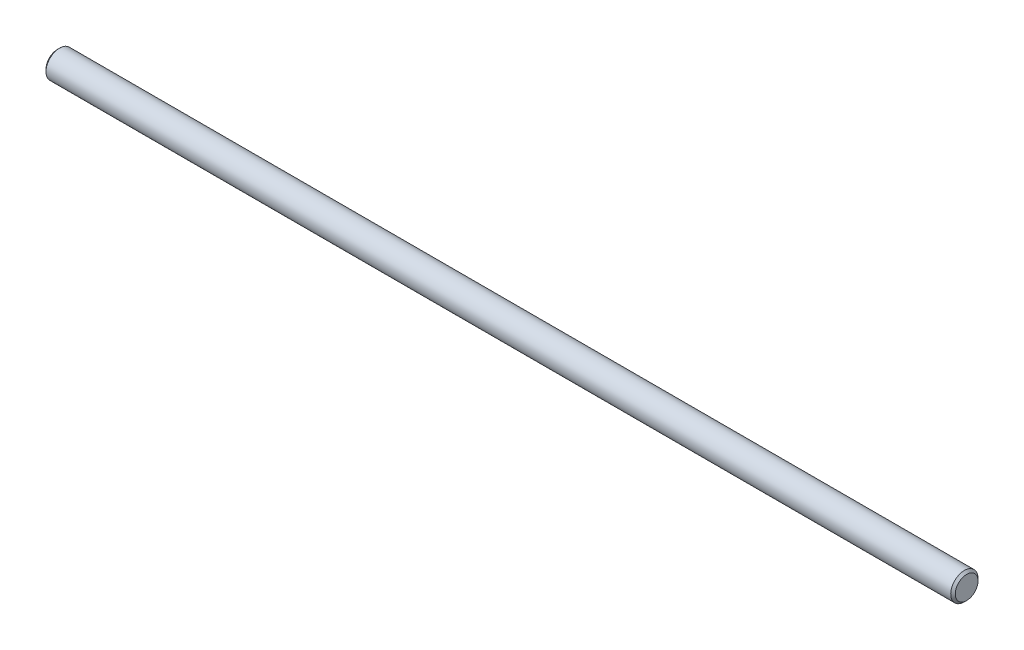
SolidWorks part; units mm, degrees
ref_plane "Płaszczyzna przednia" through (0, 0, 0) normal (0, 0, 1) x (1, 0, 0)
ref_plane "Płaszczyzna górna" through (0, 0, 0) normal (0, 1, 0) x (1, 0, 0)
ref_plane "Płaszczyzna prawa" through (0, 0, 0) normal (1, 0, 0) x (0, 0, -1)
ref_plane "Plane1" through (0, 0, 0) normal (0, 0, -1) x (-1, 0, 0)
sketch "Sketch1" plane through (0, 0, 0) normal (0, 0, -1) x (-1, 0, 0)
  line L0 (-100, 2.5731) -> (-100, 0.0731)
  line L1 (-100, 0.0731) -> (100, 0.0731)
  line L8 (100, 0.0731) -> (100, 2.5731)
  line L9 (100, 2.5731) -> (99.5, 3.0731)
  line L10 (99.5, 3.0731) -> (-99.5, 3.0731)
  line L11 (-99.5, 3.0731) -> (-100, 2.5731)
  line L12 (-100, 0.0731) -> (100, 0.0731) construction
  point P2 (-97.6017, 2.5731)
  point P3 (50, 0.182)
  point P4 (49.7368, -0.0211)
  dimension "D1" = 200
  dimension "D2" = 2.5
  dimension "D3" = 2.5
  dimension "D4" = 3
  dimension "D5" = 3
  dimension "D6" = 199
  dimension "D7" = 0.5
revolve "Revolve1" add sketch "Sketch1" angle 360 about L12
